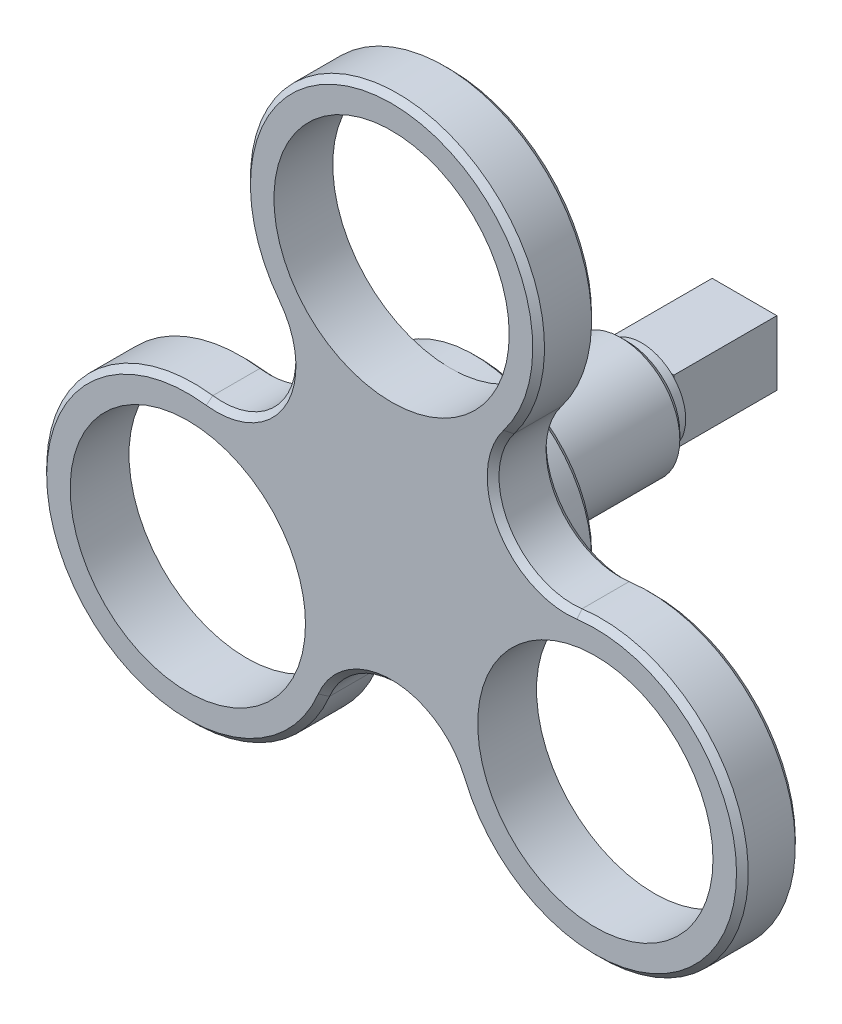
SolidWorks part; units mm, degrees
ref_plane "Piano frontale" through (0, 0, 0) normal (0, 0, 1) x (1, 0, 0)
ref_plane "Piano superiore" through (0, 0, 0) normal (0, 1, 0) x (1, 0, 0)
ref_plane "Piano destro" through (0, 0, 0) normal (1, 0, 0) x (0, 0, -1)
sketch "Schizzo1" plane through (0, 0, 0) normal (0, 0, 1) x (1, 0, 0)
  line L1 (1.1, -1.1) -> (-1.1, -1.1)
  line L2 (1.1, -1.1) -> (1.1, 1.1)
  line L3 (1.1, 1.1) -> (-1.1, 1.1)
  line L4 (-1.1, -1.1) -> (-1.1, 1.1)
  line L5 (1.1, -1.1) -> (-1.1, 1.1) construction
  line L6 (1.1, 1.1) -> (-1.1, -1.1) construction
  point P0 (0, 0)
  dimension "D1" = 2.2
  dimension "D2" = 2.2
extrude "Estrusione-Estrusione1" add sketch "Schizzo1" along normal blind 3.5
sketch "Schizzo2" plane through (0, 0, 3.5) normal (0, 0, 1) x (1, 0, 0)
  circle A0 centre (0, 0) radius 1.5
  dimension "D1" = 3
extrude "Estrusione-Estrusione2" add sketch "Schizzo2" along normal blind 0.5
sketch "Schizzo3" plane through (0, 0, 4) normal (0, 0, 1) x (1, 0, 0)
  circle A0 centre (0, 0) radius 2
  dimension "D1" = 4
extrude "Estrusione-Estrusione3" add sketch "Schizzo3" along normal blind 5
sketch "Schizzo4" plane through (0, 0, 9) normal (0, 0, 1) x (1, 0, 0)
  circle A0 centre (0, 0) radius 4
  dimension "D1" = 8
extrude "Estrusione-Estrusione4" add sketch "Schizzo4" along normal blind 1
sketch "Schizzo5" plane through (0, 0, 10) normal (0, 0, 1) x (1, 0, 0)
  line L0 (0, 8) -> (0, 0) construction
  circle A0 centre (0, 0) radius 8 construction
  circle A1 centre (0, 8) radius 4
  arc A2 (3.9677, 4.9574) -> (-3.9677, 4.9574) centre (0, 8) ccw
  circle A3 centre (0, 0) radius 8 construction
  arc A4 (2.3094, -5.9149) -> (6.2771, 0.9574) centre (6.9282, -4) ccw
  circle A5 centre (6.9282, -4) radius 4
  circle A6 centre (0, 0) radius 8 construction
  arc A7 (-6.2771, 0.9574) -> (-2.3094, -5.9149) centre (-6.9282, -4) ccw
  circle A8 centre (-6.9282, -4) radius 4
  arc A9 (3.9677, 4.9574) -> (6.2771, 0.9574) centre (5.9516, 3.4361) ccw
  arc A10 (2.3094, -5.9149) -> (-2.3094, -5.9149) centre (0, -6.8723) ccw
  arc A11 (-6.2771, 0.9574) -> (-3.9677, 4.9574) centre (-5.9516, 3.4361) ccw
  point P17 (-5.8421, 4.347)
  point P18 (-7.8431, 3.4361)
  dimension "D1" = 16
  dimension "D2" = 8
  dimension "D3" = 10
  dimension "D5" = 5
  dimension "D4" = 3
  dimension "D6" = 3
extrude "Estrusione-Estrusione5" add sketch "Schizzo5" along normal blind 2
chamfer "Smusso1" distance 0.2 angle 45 14 edges at (0, -4.3723, 12) (11.2583, -6.5, 12) (-11.2583, -6.5, 12) (3.7865, 2.1861, 12) (-3.7865, 2.1861, 12) (0, 13, 12) (0, -4.3723, 10) (11.2583, -6.5, 10) (-11.2583, -6.5, 10) (3.7865, 2.1861, 10) (-3.7865, 2.1861, 10) (0, 13, 10) (4, 0, 9) (2, 0, 4)
